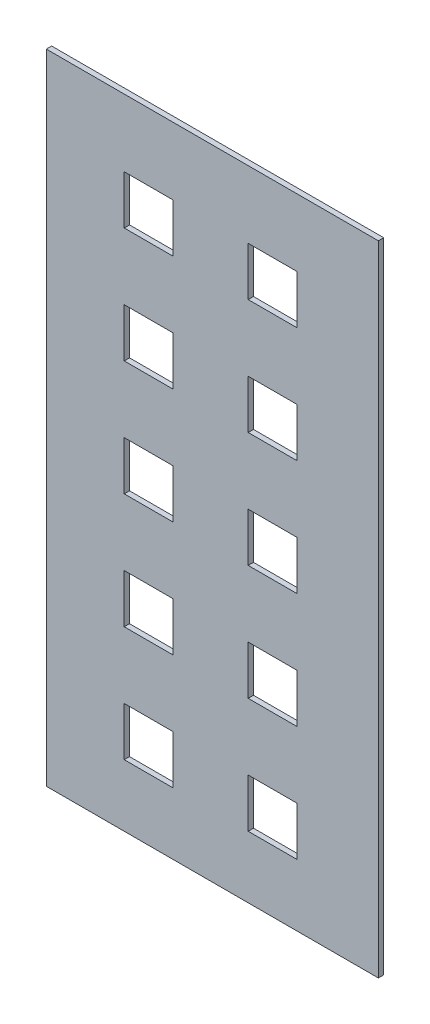
SolidWorks part; units mm, degrees
ref_plane "Front Plane" through (0, 0, 0) normal (1, 0, 0) x (0, 1, 0)
ref_plane "Top Plane" through (0, 0, 0) normal (0, 0, 1) x (0, 1, 0)
ref_plane "Right Plane" through (0, 0, 0) normal (0, 1, 0) x (-1, 0, 0)
sketch "Sketch1" plane through (0, 0, 0) normal (0, 0, 1) x (0, 1, 0)
  line L0 (0, 47.625) -> (183.134, 47.625) construction
  line L1 (0, 0) -> (183.134, 0)
  line L2 (0, 0) -> (0, 95.25)
  line L3 (0, 95.25) -> (183.134, 95.25)
  line L4 (183.134, 0) -> (183.134, 95.25)
  line L5 (17.78, 72.898) -> (31.75, 72.898)
  line L6 (17.78, 72.898) -> (17.78, 58.928)
  line L7 (17.78, 58.928) -> (31.75, 58.928)
  line L8 (31.75, 72.898) -> (31.75, 58.928)
  line L9 (50.8, 72.898) -> (50.8, 58.928)
  line L10 (50.8, 72.898) -> (64.77, 72.898)
  line L11 (64.77, 72.898) -> (64.77, 58.928)
  line L12 (50.8, 58.928) -> (64.77, 58.928)
  line L13 (83.82, 72.898) -> (83.82, 58.928)
  line L14 (83.82, 72.898) -> (97.79, 72.898)
  line L15 (97.79, 72.898) -> (97.79, 58.928)
  line L16 (83.82, 58.928) -> (97.79, 58.928)
  line L17 (116.84, 72.898) -> (116.84, 58.928)
  line L18 (116.84, 72.898) -> (130.81, 72.898)
  line L19 (130.81, 72.898) -> (130.81, 58.928)
  line L20 (116.84, 58.928) -> (130.81, 58.928)
  line L21 (149.86, 72.898) -> (149.86, 58.928)
  line L22 (149.86, 72.898) -> (163.83, 72.898)
  line L23 (163.83, 72.898) -> (163.83, 58.928)
  line L24 (149.86, 58.928) -> (163.83, 58.928)
  line L25 (50.8, 37.338) -> (50.8, 23.368)
  line L26 (50.8, 37.338) -> (64.77, 37.338)
  line L27 (64.77, 37.338) -> (64.77, 23.368)
  line L28 (50.8, 23.368) -> (64.77, 23.368)
  line L29 (83.82, 37.338) -> (83.82, 23.368)
  line L30 (83.82, 37.338) -> (97.79, 37.338)
  line L31 (97.79, 37.338) -> (97.79, 23.368)
  line L32 (83.82, 23.368) -> (97.79, 23.368)
  line L33 (116.84, 37.338) -> (116.84, 23.368)
  line L34 (116.84, 37.338) -> (130.81, 37.338)
  line L35 (130.81, 37.338) -> (130.81, 23.368)
  line L36 (116.84, 23.368) -> (130.81, 23.368)
  line L37 (149.86, 37.338) -> (149.86, 23.368)
  line L38 (149.86, 37.338) -> (163.83, 37.338)
  line L39 (163.83, 37.338) -> (163.83, 23.368)
  line L40 (149.86, 23.368) -> (163.83, 23.368)
  line L41 (17.78, 37.338) -> (17.78, 23.368)
  line L42 (17.78, 37.338) -> (31.75, 37.338)
  line L43 (31.75, 37.338) -> (31.75, 23.368)
  line L44 (17.78, 23.368) -> (31.75, 23.368)
  dimension "D1" = 95.25
  dimension "D2" = 183.134
  dimension "D3" = 13.97
  dimension "D4" = 13.97
  dimension "D5" = 17.78
  dimension "D6" = 22.352
  dimension "D7" = 5
  dimension "D8" = 2
extrude "Boss-Extrude1" add sketch "Sketch1" along normal blind 1.524
